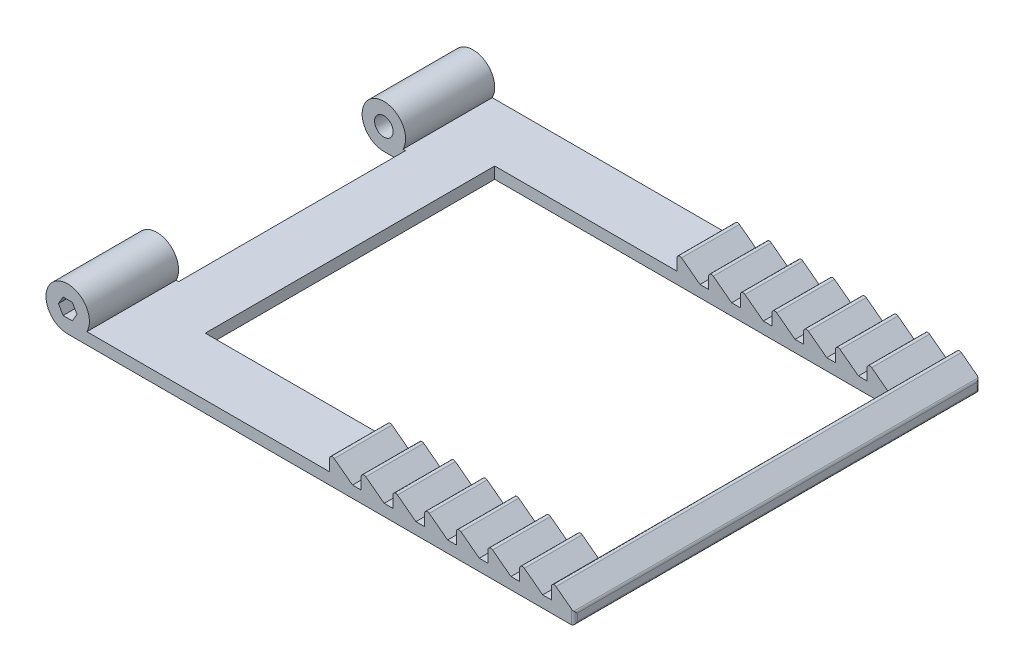
SolidWorks part; units mm, degrees
ref_plane "前视基准面" through (0, 0, 0) normal (0, 0, 1) x (1, 0, 0)
ref_plane "上视基准面" through (0, 0, 0) normal (0, 1, 0) x (1, 0, 0)
ref_plane "右视基准面" through (0, 0, 0) normal (1, 0, 0) x (0, 0, -1)
other "Configuration Table"
sketch "草图1" plane through (0, 0, 0) normal (0, 0, 1) x (1, 0, 0)
  line L0 (0, 0) -> (175, 0)
  line L1 (175, 0) -> (175, 4)
  line L2 (167.0557, 4) -> (164.0534, 4)
  line L4 (175, 4) -> (167.0557, 10)
  line L5 (167.0557, 10) -> (167.0557, 4)
  line L7 (164.0534, 4) -> (156.1091, 10)
  line L8 (156.1091, 10) -> (156.1091, 4)
  line L10 (153.1068, 4) -> (145.1625, 10)
  line L11 (145.1625, 10) -> (145.1625, 4)
  line L13 (142.1602, 4) -> (134.2159, 10)
  line L14 (134.2159, 10) -> (134.2159, 4)
  line L16 (131.2136, 4) -> (123.2693, 10)
  line L17 (123.2693, 10) -> (123.2693, 4)
  line L19 (120.267, 4) -> (112.3227, 10)
  line L20 (112.3227, 10) -> (112.3227, 4)
  line L22 (109.3204, 4) -> (101.3761, 10)
  line L23 (101.3761, 10) -> (101.3761, 4)
  line L25 (98.3738, 4) -> (90.4295, 10)
  line L26 (90.4295, 10) -> (90.4295, 4)
  line L29 (90.4295, 4) -> (72.4272, 4)
  line L30 (101.3761, 4) -> (98.3738, 4)
  line L31 (112.3227, 4) -> (109.3204, 4)
  line L32 (123.2693, 4) -> (120.267, 4)
  line L33 (134.2159, 4) -> (131.2136, 4)
  line L34 (145.1625, 4) -> (142.1602, 4)
  line L35 (156.1091, 4) -> (153.1068, 4)
  line L37 (3.2, 7.5) -> (1.6, 10.2713)
  line L38 (1.6, 10.2713) -> (-1.6, 10.2713)
  line L39 (-1.6, 10.2713) -> (-3.2, 7.5)
  line L40 (-3.2, 7.5) -> (-1.6, 4.7287)
  line L41 (-1.6, 4.7287) -> (1.6, 4.7287)
  line L42 (1.6, 4.7287) -> (3.2, 7.5)
  line L46 (54.611, 4) -> (6.6332, 4)
  line L47 (65.5576, 4) -> (61.4806, 4)
  line L48 (54.611, 4) -> (61.4806, 4)
  line L49 (65.5576, 4) -> (72.4272, 4)
  arc A0 (6.6332, 4) -> (0, 0) centre (0, 7.5) ccw
  circle A2 centre (0, 7.5) radius 3.2 construction
  dimension "D2" = 4.3
  dimension "D4" = 6.4
  dimension "D3" = 4
  dimension "D5" = 175
  dimension "D6" = 6
  dimension "D1" = 8
extrude "凸台-拉伸1" add sketch "草图1" against normal blind 140
sketch "草图2" plane through (0, 0, 0) normal (1, 0, 0) x (0, 0, -1)
  line L0 (140, 4) -> (0, 4) construction
  line L1 (140, 4) -> (0, 4) construction
  line L2 (140, 15) -> (0, 15) construction
  line L3 (30.8, 4) -> (109.2, 4)
  line L4 (30.8, 4) -> (30.8, 15)
  line L5 (30.8, 15) -> (109.2, 15)
  line L6 (109.2, 4) -> (109.2, 15)
  line L7 (30.8, 9.5) -> (0, 9.5) construction
  line L8 (109.2, 9.5) -> (140, 9.5) construction
  line L9 (140, 4) -> (140, 18.1242) construction
  line L12 (0, 4) -> (0, 18) construction
  point P12 (0, 0)
  dimension "D1" = 30.8
extrude "切除-拉伸1" cut sketch "草图2" against normal blind 20 and the other way blind 20
sketch "草图3" plane through (0, 0, -109.2) normal (0, 0, 1) x (1, 0, 0)
  line L7 (-6.6332, 4) -> (6.6332, 4)
  line L14 (-6.6332, 4) -> (6.6332, 4) construction
  circle A0 centre (0, 7.5) radius 3.2
  arc A1 (6.6332, 4) -> (-6.6332, 4) centre (0, 7.5) ccw
  arc A2 (6.6332, 4) -> (-6.6332, 4) centre (0, 7.5) ccw construction
  dimension "D1" = 0
extrude "切除-拉伸2" cut sketch "草图3" along normal up to surface (78.4 mm away) and the other way through all up to face at (0, 9.5, -30.8)
fillet "圆角1" radius 1 12 edges at (175, 2, -140) (175, 2, 0) (175, 0, -70) (175, 4, -70) (167.0557, 10, -70) (156.1091, 10, -70) (145.1625, 10, -70) (134.2159, 10, -70) (123.2693, 10, -70) (112.3227, 10, -70) (101.3761, 10, -70) (90.4295, 10, -70)
sketch "草图4" plane through (0, 4, 0) normal (0, 1, 0) x (1, 0, 0)
  line L0 (7.5, 109.2) -> (7.5, 30.8)
  line L1 (7.5, 30.8) -> (-6.6332, 30.8)
  line L2 (-6.6332, 30.8) -> (-6.6332, 109.2)
  line L3 (-6.6332, 109.2) -> (7.5, 109.2)
extrude "切除-拉伸3" cut sketch "草图4" against normal through all
sketch "草图5" plane through (0, 4, 0) normal (0, 1, 0) x (1, 0, 0)
  line L1 (27.5, 120) -> (164.0443, 120)
  line L2 (27.5, 120) -> (27.5, 20)
  line L3 (27.5, 20) -> (164.0443, 20)
  line L5 (66.1729, 140) -> (66.1729, 120) construction
  line L6 (90.4295, 140) -> (6.6332, 140) construction
  line L7 (66.1729, 20) -> (66.1729, 0) construction
  line L8 (-8.25, 0) -> (8.25, 0) construction
  line L9 (7.5, 70) -> (27.5, 70) construction
  line L10 (7.5, 30.8) -> (7.5, 109.2) construction
  line L11 (164.0443, 120) -> (164.0443, 20)
  dimension "D1" = 20
  dimension "D2" = 20
extrude "切除-拉伸4" cut sketch "草图5" against normal through all and the other way through all
